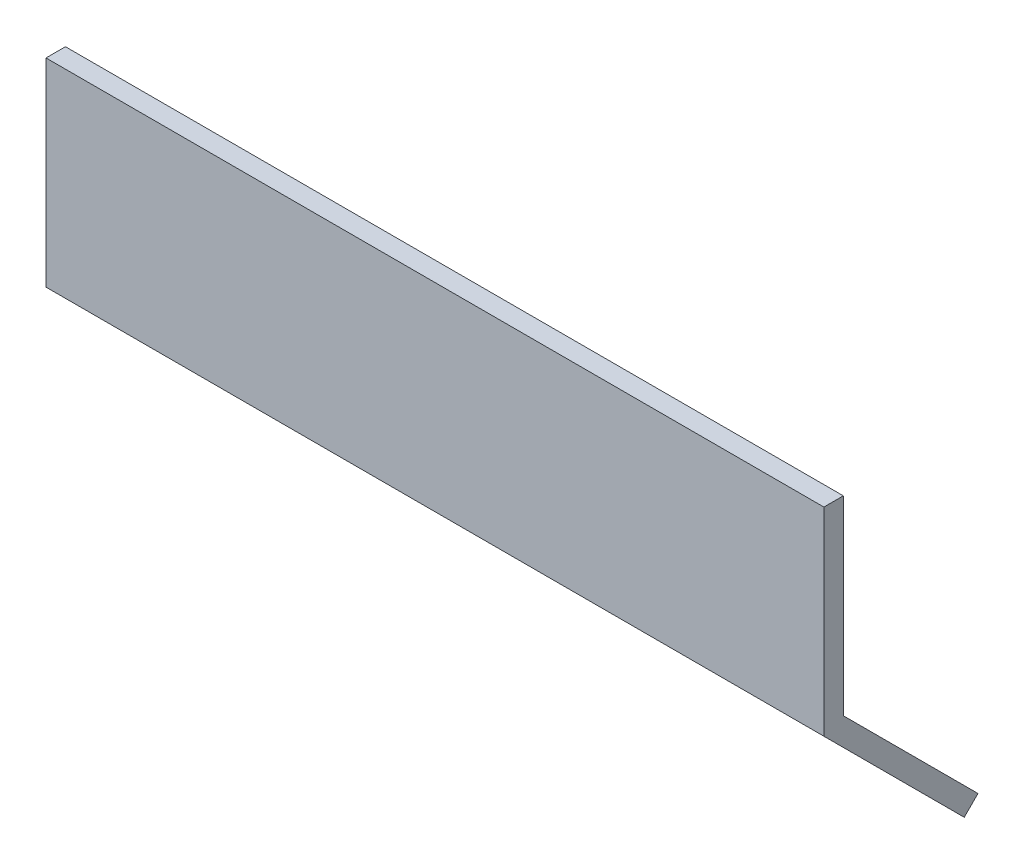
SolidWorks part; units mm, degrees
ref_plane "Front Plane" through (0, 0, 0) normal (0, 0, 1) x (1, 0, 0)
ref_plane "Top Plane" through (0, 0, 0) normal (0, 1, 0) x (1, 0, 0)
ref_plane "Right Plane" through (0, 0, 0) normal (1, 0, 0) x (0, 0, -1)
sketch "Sketch2" plane through (0, 0, 0) normal (1, 0, 0) x (0, 0, -1)
  line L0 (0, 50) -> (0, 0)
  line L1 (0, 0) -> (35.3553, -35.3553)
  dimension "D1" = 50
  dimension "D2" = 50
  dimension "D3" = 135
extrude "Extrude-Thin1" add sketch "Sketch2" along normal blind 200 thin thin type mid plane wall 5
sketch "Sketch3" plane through (0, 1.7678, -1.7678) normal (0, 0.7071, -0.7071) x (1, 0, 0)
  line L0 (200, 1.0355) -> (200, 50) construction
  line L1 (200, 50) -> (0, 50) construction
  circle A0 centre (132, 42) radius 1.5
  circle A1 centre (196, 42) radius 1.5
  point P8 (0, 0)
  dimension "D1" = 3
  dimension "D2" = 3
  dimension "D3" = 64
  dimension "D4" = 4
  dimension "D5" = 8
extrude "Cut-Extrude1" cut sketch "Sketch3" against normal up to next
